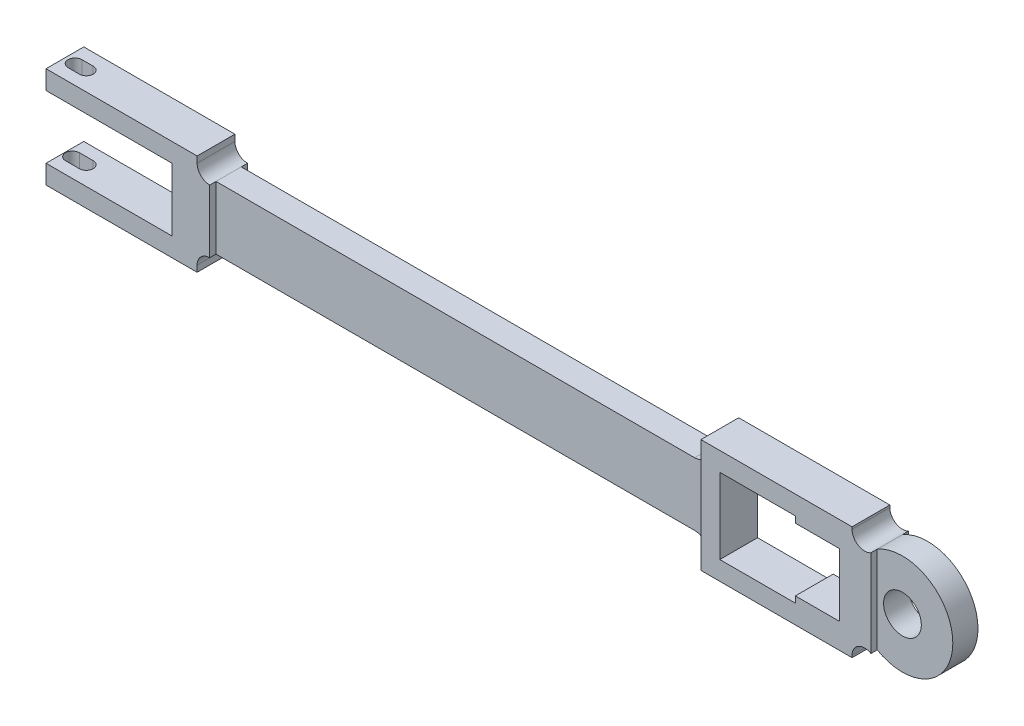
SolidWorks part; units mm, degrees
ref_plane "Plan de face" through (0, 0, 0) normal (0, 0, 1) x (1, 0, 0)
ref_plane "Plan de dessus" through (0, 0, 0) normal (0, 1, 0) x (1, 0, 0)
ref_plane "Plan de droite" through (0, 0, 0) normal (1, 0, 0) x (0, 0, -1)
sketch "Esquisse1" plane through (0, 0, 0) normal (0, 0, 1) x (1, 0, 0)
  line L0 (-10, 2.5) -> (0, 2.5)
  line L1 (0, 2.5) -> (0, 0)
  line L2 (0, 0) -> (0, -2.5)
  line L3 (0, -2.5) -> (-10, -2.5)
  line L4 (-10, -2.5) -> (-10, -4)
  line L5 (-10, -4) -> (2, -4)
  line L6 (-1000, 0) -> (49000, 0) construction
  line L7 (2, -4) -> (2, -3.5)
  line L8 (3, -2.5) -> (41, -2.5)
  line L9 (42, -3.5) -> (42, -4.5)
  line L10 (42, -4.5) -> (54, -4.5)
  line L11 (54, -4.3301) -> (54, -4.5)
  line L12 (43.5, 3) -> (43.5, -3)
  line L13 (43.5, -3) -> (49.5, -3)
  line L14 (49.5, -3) -> (49.5, -2.5)
  line L15 (49.5, -2.5) -> (53, -2.5)
  line L16 (53, -2.5) -> (53, 2.5)
  line L17 (42, 3.5) -> (42, 4.5)
  line L18 (49.5, 3) -> (49.5, 2.5)
  line L19 (43.5, 3) -> (49.5, 3)
  line L20 (42, 4.5) -> (54, 4.5)
  line L21 (49.5, 2.5) -> (53, 2.5)
  line L22 (-10, 4) -> (2, 4)
  line L23 (2, 4) -> (2, 3.5)
  line L24 (3, 2.5) -> (41, 2.5)
  line L25 (-10, 2.5) -> (-10, 4)
  arc A0 (3, -2.5) -> (2, -3.5) centre (3, -3.5) ccw
  arc A1 (42, -3.5) -> (41, -2.5) centre (41, -3.5) ccw
  arc A2 (55.5, 3.4641) -> (55.5, -3.4641) centre (57.5, 0) cw
  arc A3 (55.5, -3.4641) -> (54, -4.3301) centre (55, -4.3301) ccw
  circle A4 centre (57.5, 0) radius 1.5
  arc A5 (42, 3.5) -> (41, 2.5) centre (41, 3.5) cw
  arc A6 (55.5, 3.4641) -> (54, 4.3301) centre (55, 4.3301) cw
  arc A7 (3, 2.5) -> (2, 3.5) centre (3, 3.5) cw
  point P5 (-3.5, 0)
  point P10 (49.5, 0)
  point P16 (2, -2.5)
  point P20 (42, -2.5)
  point P22 (57.5, 0)
  point P37 (43.5, 0)
  point P45 (53, 0)
  dimension "D10" = 1
  dimension "D14" = 1
  dimension "D17" = 4
  dimension "D18" = 1
  dimension "D19" = 1.5
  dimension "D1" = 0
  dimension "D2" = 10
  dimension "D3" = 10
  dimension "D4" = 2.5
  dimension "D5" = 2.5
  dimension "D6" = 1.5
  dimension "D7" = 6.5
  dimension "D8" = 53
  dimension "D9" = 1.5
  dimension "D11" = 12
  dimension "D12" = 7.5
  dimension "D13" = 4.5
  dimension "D15" = 12
  dimension "D16" = 8
  dimension "D20" = 1.5
  dimension "D21" = 3
  dimension "D22" = 6
  dimension "D23" = 0.5
  dimension "D24" = 3.5
extrude "Boss.-Extru.3" add sketch "Esquisse1" along normal blind 3 contours L6 L2 L3 L4 L5 L7 A0 L8 A1 L9 L10 L11 A3 A2 A4 L16 L15 L14 L13 L12
mirror "Symétrie2" about plane through (0, 0, 3) normal (0, 1, 0) of "Boss.-Extru.3"
sketch "Esquisse2" plane through (0, 4, 0) normal (0, 1, 0) x (1, 0, 0)
  line L0 (-9.2, -1.5) -> (-8.3, -1.5) construction
  line L1 (-9.2, -0.95) -> (-8.3, -0.95)
  line L2 (-9.2, -2.05) -> (-8.3, -2.05)
  line L3 (-10, 0) -> (2, 0) construction
  arc A0 (-9.2, -0.95) -> (-9.2, -2.05) centre (-9.2, -1.5) ccw
  arc A1 (-8.3, -2.05) -> (-8.3, -0.95) centre (-8.3, -1.5) ccw
  point P2 (-8.75, -1.5)
  dimension "D3" = 0.55
  dimension "D1" = 8.3
  dimension "D2" = 0.9
  dimension "D4" = 1.5
extrude "Enlèv. mat.-Extru.1" cut sketch "Esquisse2" against normal blind 3 and the other way through all
sketch "Esquisse3" plane through (0, -4, 0) normal (0, -1, 0) x (1, 0, 0)
  line L0 (-9.4, 1.5) -> (-8.3, 1.5) construction
  line L1 (-9.4, 2.05) -> (-8.3, 2.05)
  line L2 (-9.4, 0.95) -> (-8.3, 0.95)
  line L3 (-10, 0) -> (2, 0) construction
  arc A0 (-9.4, 2.05) -> (-9.4, 0.95) centre (-9.4, 1.5) ccw
  arc A1 (-8.3, 0.95) -> (-8.3, 2.05) centre (-8.3, 1.5) ccw
  point P2 (-8.85, 1.5)
  dimension "D1" = 0.55
  dimension "D2" = 1.5
  dimension "D3" = 1.1
  dimension "D4" = 8.3
extrude "Enlèv. mat.-Extru.2" cut sketch "Esquisse3" against normal blind 3
sketch "Esquisse5" plane through (0, -4.5, 0) normal (0, -1, 0) x (1, 0, 0)
  line L0 (-953.4034, 1.5) -> (49046.5966, 1.5) construction
  line L2 (61.5, 2.5) -> (55.5, 2.5)
  line L3 (61.5, 0) -> (61.5, 3) construction
  line L4 (55.5, 3) -> (55.5, 0) construction
  line L5 (54, 3) -> (42, 3)
  line L6 (42, 3) -> (42, 2.5)
  line L7 (42, 3) -> (42, 0) construction
  line L8 (42, 2.5) -> (41, 2.5)
  line L9 (41, 3) -> (41, 0) construction
  line L10 (41, 2.5) -> (3, 2.5)
  line L11 (3, 3) -> (3, 0) construction
  line L12 (3, 2.5) -> (3, 3)
  line L13 (3, 3) -> (-10, 3)
  line L14 (-10, 3) -> (-10, 0)
  line L15 (-10, 3) -> (-10, 0) construction
  line L16 (61.5, 2.5) -> (61.5, 0.5)
  line L17 (55.5, 2.5) -> (55.5, 3)
  line L18 (55.5, 3) -> (54, 3)
  line L19 (42, 0) -> (42, 0.5)
  line L20 (42, 0.5) -> (41, 0.5)
  line L21 (54, 0) -> (42, 0)
  line L22 (55.5, 0.5) -> (55.5, 0)
  line L23 (55.5, 0) -> (54, 0)
  line L24 (61.5, 0.5) -> (55.5, 0.5)
  line L25 (3, 0) -> (-10, 0)
  line L26 (3, 0.5) -> (3, 0)
  line L27 (41, 0.5) -> (3, 0.5)
  line L28 (3, 3) -> (42, 3)
  line L29 (42, 0) -> (3, 0)
  line L30 (55.5, 0) -> (61.5, 0)
  line L31 (55.5, 0) -> (61.5, 0) construction
  line L32 (61.5, 0) -> (61.5, 0.5)
  line L33 (55.5, 3) -> (61.5, 3)
  line L34 (61.5, 3) -> (55.5, 3) construction
  line L35 (61.5, 3) -> (61.5, 2.5)
  point P34 (61.5, 1.5)
  point P41 (-10, 1.5)
  line M26 (42, 3) -> (42, 0)
  dimension "D2" = 1
  dimension "D3" = 0.5
extrude "Enlèv. mat.-Extru.4" cut sketch "Esquisse5" against normal through all contours L28 L12 L10 L8 M26 | L29 L20 L27 L26 M26 | L35 L33 L17 L2 | L30 L32 L24 L22
